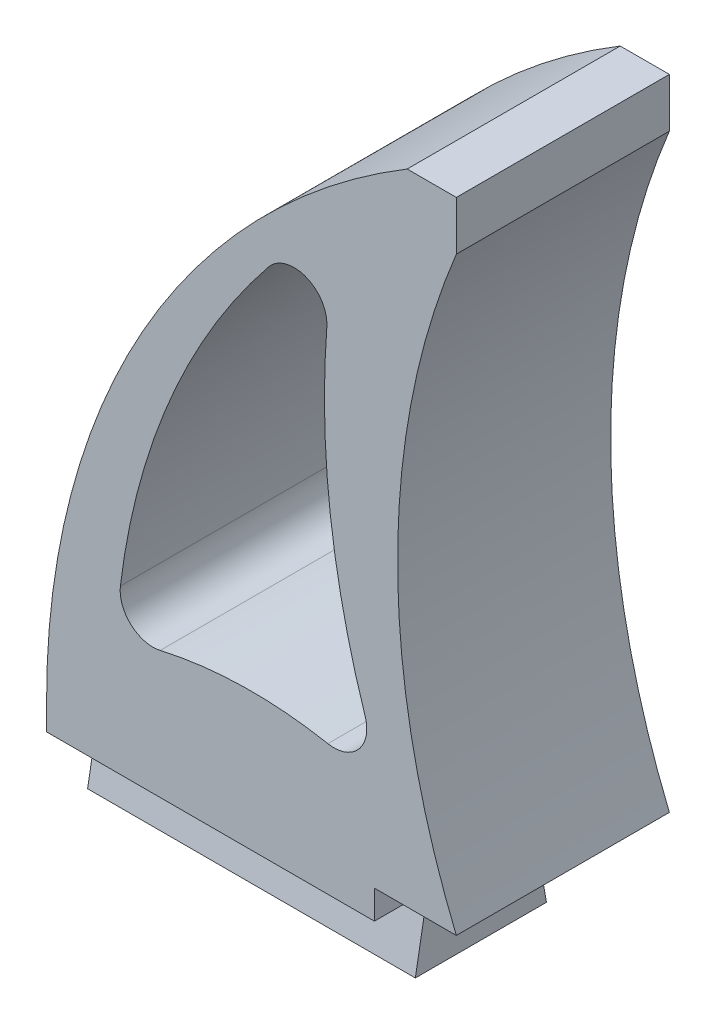
SolidWorks part; units mm, degrees
ref_plane "前视基准面" through (0, 0, 0) normal (0, 0, 1) x (1, 0, 0)
ref_plane "上视基准面" through (0, 0, 0) normal (0, 1, 0) x (1, 0, 0)
ref_plane "右视基准面" through (0, 0, 0) normal (1, 0, 0) x (0, 0, -1)
sketch "草图1" plane through (0, 0, 0) normal (0, 0, 1) x (1, 0, 0)
  line L0 (0, 0) -> (0, 6)
  line L1 (22, 45) -> (25, 45)
  line L2 (25, 45) -> (25, 42)
  line L3 (25, 6) -> (20, 6)
  line L4 (20, 6) -> (20, 0)
  line L5 (20, 0) -> (0, 0)
  arc A0 (0, 6) -> (22, 45) centre (45.5682, 6) cw
  arc A1 (25, 42) -> (25, 6) centre (68.4166, 24) ccw
  point P9 (0, 0)
  dimension "D6" = 47
  dimension "D7" = 25
  dimension "D1" = 6
  dimension "D2" = 20
  dimension "D3" = 5
  dimension "D4" = 3
  dimension "D5" = 3
  dimension "D8" = 39
extrude "凸台-拉伸1" add sketch "草图1" along normal mid plane 13
sketch "草图2" plane through (0, 0, 0) normal (-1, 0, 0) x (0, 0, 1)
  line L0 (0, 0) -> (0, 14.5759) construction
  line L1 (6.5, 0) -> (-6.5, 0) construction
  line L2 (6.5, 4.2535) -> (3.25, 4.2535)
  line L3 (6.5, 6) -> (6.5, 0) construction
  line L4 (3.25, 4.2535) -> (4, 0)
  line L5 (4, 0) -> (6.5, 0)
  line L6 (6.5, 0) -> (6.5, 4.2535)
  line L7 (-4, 0) -> (-6.5, 0)
  line L8 (-3.25, 4.2535) -> (-4, 0)
  line L9 (-6.5, 4.2535) -> (-3.25, 4.2535)
  line L10 (-6.5, 0) -> (-6.5, 4.2535)
  dimension "D1" = 3.25
  dimension "D2" = 4
  dimension "D3" = 80
extrude "切除-拉伸1" cut sketch "草图2" against normal through all
sketch "草图3" plane through (0, 0, 6.5) normal (0, 0, 1) x (1, 0, 0)
  line L0 (25, 6) -> (0, 6) construction
  line L1 (0, 6) -> (0, 4.2535) construction
  line L2 (12.5, 6) -> (12.5, 30.8591) construction
  line L3 (0, 4.2535) -> (20, 4.2535) construction
  arc A0 (6.9325, 12.0261) -> (17.1628, 12.2153) centre (12.5, -12.3461) cw
  arc A1 (4.5015, 14.2155) -> (13.5489, 35.6029) centre (46.199, 9.1838) cw
  arc A2 (17.0978, 34.192) -> (19.4364, 14.8028) centre (66.9514, 30.3696) ccw
  arc A3 (17.1628, 12.2153) -> (19.4364, 14.8028) centre (17.5358, 14.1802) ccw
  arc A4 (6.9325, 12.0261) -> (4.5015, 14.2155) centre (6.4871, 13.9759) cw
  arc A5 (13.5489, 35.6029) -> (17.0978, 34.192) centre (15.1036, 34.3449) cw
  point P2 (0, 0)
  point P3 (0, 0)
  point P15 (0, 0)
  point P18 (12.5, 40.2535)
  point P19 (12.5, 40.2535)
  point P20 (12.5, 40.2535)
  point P21 (0, 0)
  point P22 (12.5, 40.2535)
  point P23 (17.9381, 34.8988)
  point P26 (20.75, 11.2535)
  point P29 (4.25, 11.2535)
  point P32 (17.9381, 40.2535)
  dimension "D3" = 25
  dimension "D4" = 13.6881
  dimension "D5" = 42
  dimension "D6" = 50
  dimension "D8" = 2
  dimension "D1" = 16.5
  dimension "D2" = 7
  dimension "D7" = 29
extrude "切除-拉伸2" cut sketch "草图3" against normal through all
